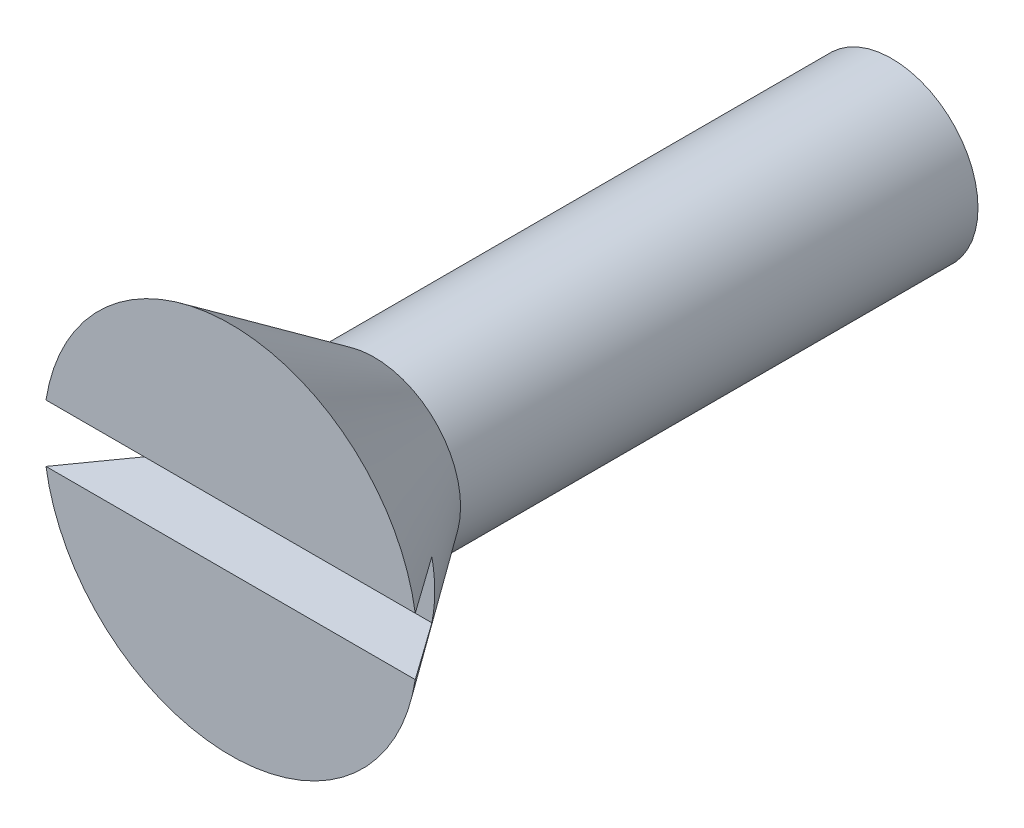
SolidWorks part; units mm, degrees
material "Alloy Steel"
ref_plane "Front Plane" through (0, 0, 0) normal (0, 0, 1) x (1, 0, 0)
ref_plane "Top Plane" through (0, 0, 0) normal (0, 1, 0) x (1, 0, 0)
ref_plane "Right Plane" through (0, 0, 0) normal (1, 0, 0) x (0, 0, -1)
sketch "Sketch1" plane through (0, 0, 0) normal (1, 0, 0) x (0, 0, -1)
  line L0 (-20.1828, 0) -> (20.1828, 0) construction
  line L1 (10.5824, 0) -> (8.8504, 3)
  line L2 (8.8504, 3) -> (-9.1496, 3)
  line L3 (-9.1496, 3) -> (-14.1496, 6.5)
  line L4 (-14.1496, 6.5) -> (-14.1496, 0)
  line L5 (10.5824, 0) -> (-14.1496, 0)
  point P4 (0, 0)
  dimension "D1" = 18
  dimension "D2" = 60
  dimension "D3" = 6
  dimension "D4" = 5
  dimension "D5" = 6.5
  dimension "D6" = 8.8504
revolve "Revolve1" add sketch "Sketch1" angle 360 about L0
sketch "Sketch3" plane through (0, 0, 0) normal (1, 0, 0) x (0, 0, -1)
  line L0 (-14.1496, 6.5) -> (-14.1496, -6.5) construction
  line L1 (-16.1496, 1) -> (-12.1496, 1)
  line L2 (-16.1496, 1) -> (-16.1496, -1)
  line L3 (-16.1496, -1) -> (-12.1496, -1)
  line L4 (-12.1496, 1) -> (-12.1496, -1)
  line L5 (-14.1496, -1) -> (-14.1496, 1) construction
  line L6 (-16.1496, 0) -> (-12.1496, 0) construction
  point P0 (-14.1496, 0)
  dimension "D1" = 2
  dimension "D2" = 2
extrude "Cut-Extrude1" cut sketch "Sketch3" against normal through all and the other way through all
